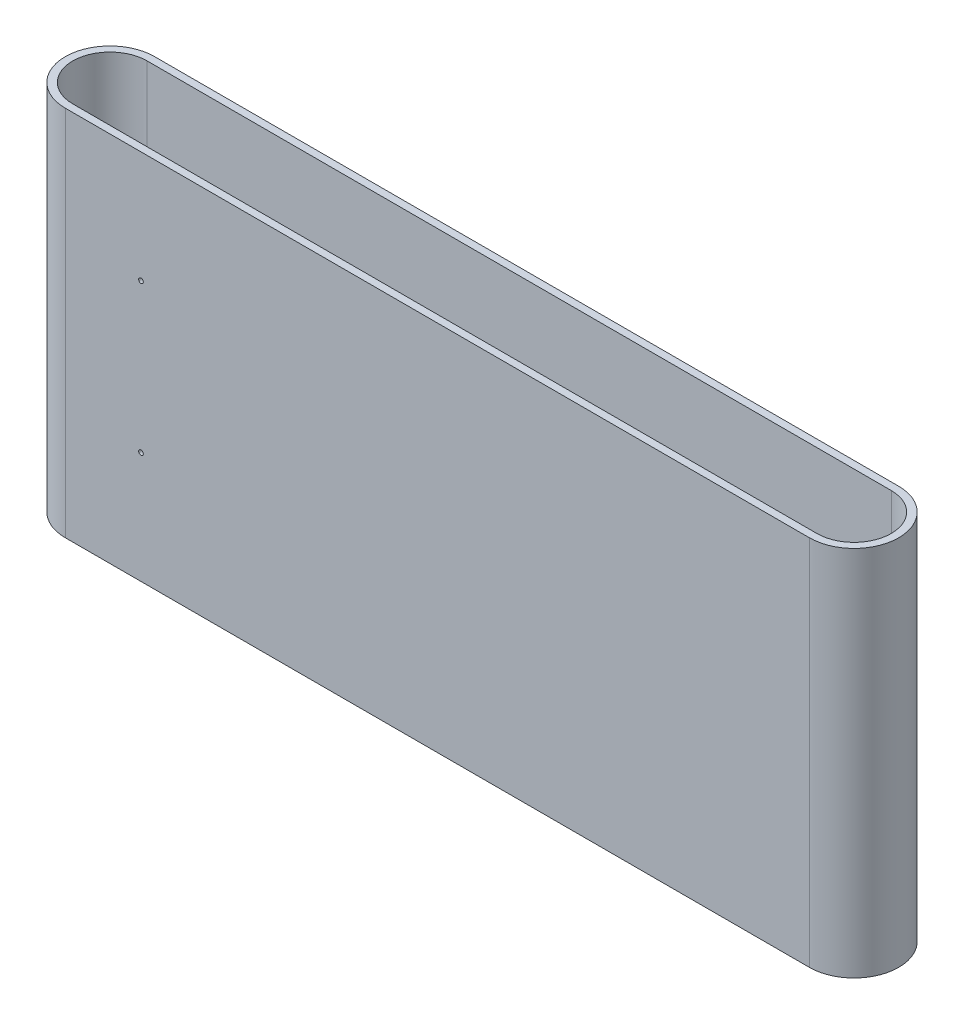
SolidWorks part; units mm, degrees
ref_plane "前视基准面" through (0, 0, 0) normal (0, 0, 1) x (1, 0, 0)
ref_plane "上视基准面" through (0, 0, 0) normal (0, 1, 0) x (1, 0, 0)
ref_plane "右视基准面" through (0, 0, 0) normal (1, 0, 0) x (0, 0, -1)
sketch "草图1" plane through (0, 0, 0) normal (0, 1, 0) x (1, 0, 0)
  line L0 (0, 20) -> (400, 20)
  line L1 (0, -20) -> (400, -20)
  arc A0 (0, 20) -> (0, -20) centre (0, 0) ccw
  arc A1 (400, -20) -> (400, 20) centre (400, 0) ccw
  dimension "D1" = 40
  dimension "D2" = 400
extrude "拉伸-薄壁1" add sketch "草图1" along normal blind 200 thin thin type one direction wall 4
hole_wizard "M3 螺纹孔1" positions "草图2" profile "草图3" tap size "M3" standard "GB" end condition through all
sketch "草图2" plane through (0, 0, 24) normal (0, 0, 1) x (1, 0, 0)
  line L0 (0, 200) -> (400, 200) construction
  point P0 (40.6827, 140)
  point P2 (40.6827, 60)
  dimension "D1" = 60
  dimension "D2" = 80
sketch "草图3" plane through (40.6827, 140, 24) normal (1, 0, 0) x (0, -1, 0)
  line L0 (0, 0) -> (0, 48)
  line L1 (0, 48) -> (1.25, 48)
  line L2 (1.25, 48) -> (1.25, 0)
  line L5 (1.25, 0) -> (0, 0)
  line L11 (0, -6.35) -> (0, 107.95) construction
  dimension "通孔螺纹孔钻头直径" = 2.5
  dimension "通孔螺纹孔钻头深度" = 48
cosmetic thread "孔螺蚊线1" parameters "D2"=3
cosmetic thread "孔螺蚊线2" parameters "D2"=3
